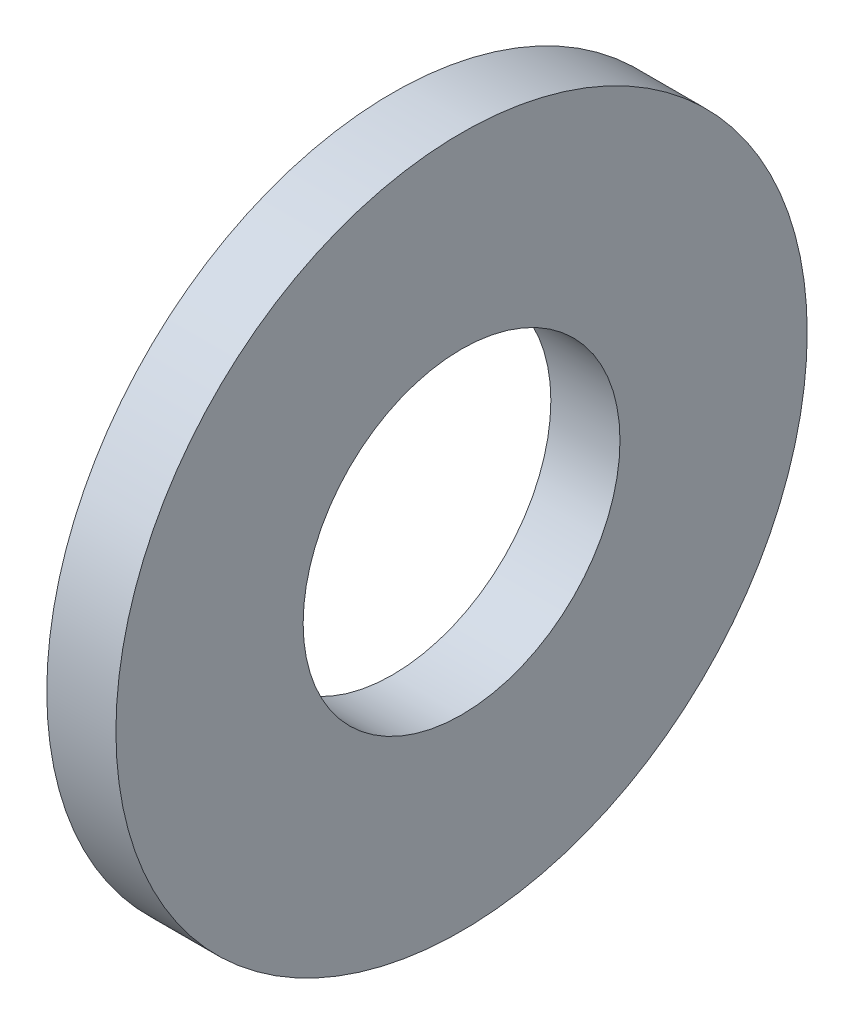
SolidWorks part; units mm, degrees
ref_plane "Plane1" through (0, 0, 0) normal (0, 0, 1) x (1, 0, 0)
ref_plane "Plane2" through (0, 0, 0) normal (0, 1, 0) x (1, 0, 0)
ref_plane "Plane3" through (0, 0, 0) normal (1, 0, 0) x (0, 0, -1)
sketch "Sketch1" plane through (0, 0, 0) normal (1, 0, 0) x (0, 0, -1)
  circle A0 centre (0, 0) radius 1.375
  circle A1 centre (0, 0) radius 3
  dimension "Insid_dia" = 2.75
  dimension "OutsideDia" = 6
extrude "Base-Extrude" add sketch "Sketch1" along normal blind 0.6
